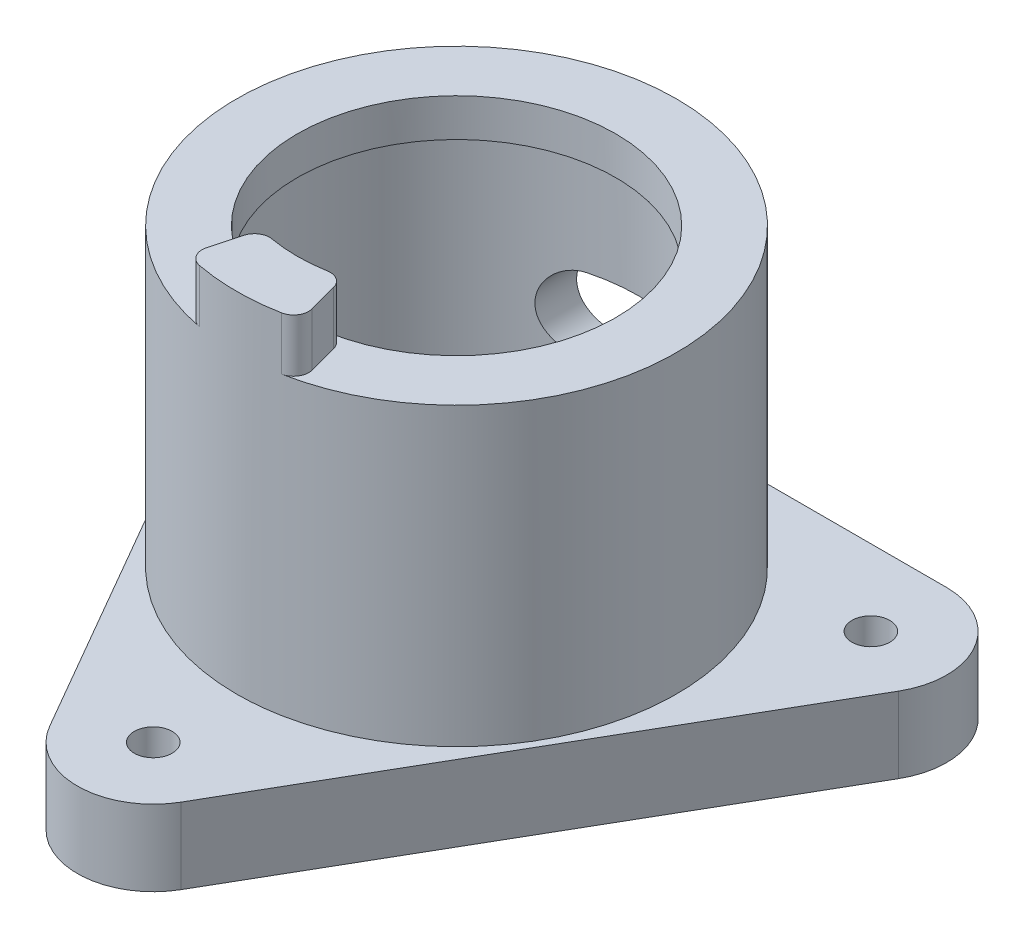
SolidWorks part; units mm, degrees
material "6061 合金"
ref_plane "前视基准面" through (0, 0, 0) normal (0, 0, 1) x (1, 0, 0)
ref_plane "上视基准面" through (0, 0, 0) normal (0, 1, 0) x (1, 0, 0)
ref_plane "右视基准面" through (0, 0, 0) normal (1, 0, 0) x (0, 0, -1)
sketch "草图1" plane through (0, 0, 0) normal (0, 1, 0) x (1, 0, 0)
  line L3 (-21.6506, 7.5) -> (-4.3301, -22.5)
  line L4 (21.6506, 7.5) -> (4.3301, -22.5)
  line L5 (17.3205, 15) -> (-17.3205, 15)
  arc A0 (-17.3205, 15) -> (-21.6506, 7.5) centre (-17.3205, 10) ccw
  arc A1 (21.6506, 7.5) -> (17.3205, 15) centre (17.3205, 10) ccw
  arc A2 (-4.3301, -22.5) -> (4.3301, -22.5) centre (0, -20) ccw
  circle A3 centre (0, 0) radius 12
  circle A4 centre (0, 0) radius 20 construction
  point P8 (0, 0)
  point P25 (0, 0)
  dimension "D1" = 3
  dimension "D2" = 24
  dimension "D3" = 40
extrude "凸台-拉伸4" add sketch "草图1" along normal blind 5
sketch "草图5" plane through (0, 5, 0) normal (0, 1, 0) x (1, 0, 0)
  circle A0 centre (0, -20) radius 1.25
  circle A1 centre (-17.3205, 10) radius 1.25
  circle A2 centre (17.3205, 10) radius 1.25
  point P11 (0, 0)
  dimension "D1" = 2.5
  dimension "D2" = 20
  dimension "D3" = 3
extrude "M3螺纹孔1" cut sketch "草图5" against normal blind 5
cosmetic thread "装饰螺纹线1" parameters "D2"=3
cosmetic thread "装饰螺纹线2" parameters "D2"=3
cosmetic thread "装饰螺纹线3" parameters "D2"=3
sketch "草图6" plane through (0, 5, 0) normal (0, 1, 0) x (1, 0, 0)
  circle A0 centre (0, 0) radius 12
  circle A1 centre (0, 0) radius 14.5
  dimension "D1" = 29
extrude "凸台-拉伸5" add sketch "草图6" along normal blind 17
sketch "草图7" plane through (0, 22, 0) normal (0, 1, 0) x (1, 0, 0)
  circle A0 centre (0, 0) radius 14.5
  circle A1 centre (0, 0) radius 10.5
  dimension "D1" = 21
  dimension "D2" = 29
extrude "凸台-拉伸6" add sketch "草图7" along normal blind 2.5
sketch "草图8" plane through (0, 24.5, 0) normal (0, 1, 0) x (1, 0, 0)
  line L0 (2.9651, -11.0661) -> (3.4845, -13.0042)
  line L2 (-2.9651, -11.0661) -> (-3.4845, -13.0042)
  arc A0 (-1.8254, -10.3401) -> (1.8254, -10.3401) centre (0, 0) ccw
  arc A1 (-2.7051, -14.2454) -> (2.7051, -14.2454) centre (0, 0) ccw
  arc A2 (2.9651, -11.0661) -> (1.8254, -10.3401) centre (1.9992, -11.3249) ccw
  arc A3 (2.7051, -14.2454) -> (3.4845, -13.0042) centre (2.5185, -13.263) ccw
  arc A4 (-2.7051, -14.2454) -> (-3.4845, -13.0042) centre (-2.5185, -13.263) cw
  arc A5 (-2.9651, -11.0661) -> (-1.8254, -10.3401) centre (-1.9992, -11.3249) cw
  dimension "D1" = 1
extrude "凸台-拉伸7" add sketch "草图8" along normal blind 3.5
sketch "草图9" plane through (0, 0, 0) normal (0, 0, 1) x (1, 0, 0)
  line L1 (-21.6506, 0) -> (-4.3301, 0) construction
  line L2 (-3, 14.5) -> (3, 14.5)
  line L3 (3, 9.5) -> (-3, 9.5)
  arc A0 (-3, 14.5) -> (-3, 9.5) centre (-3, 12) ccw
  arc A1 (3, 14.5) -> (3, 9.5) centre (3, 12) cw
  point P1 (0, 9.5)
  dimension "D1" = 5
  dimension "D2" = 6
  dimension "D3" = 12
extrude "切除-拉伸3" cut sketch "草图9" against normal through all
